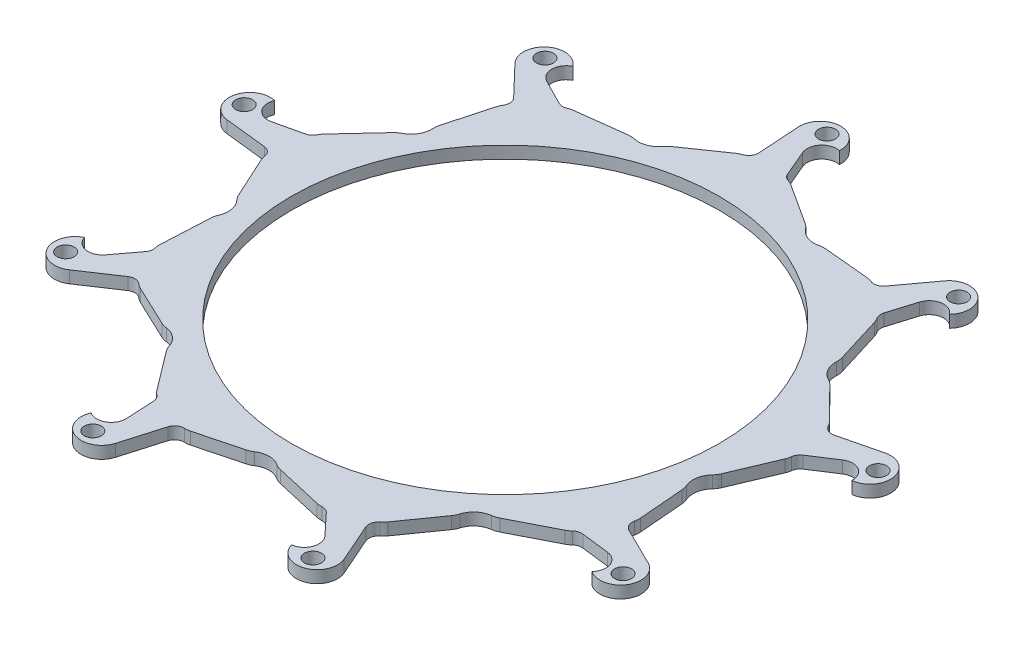
SolidWorks part; units mm, degrees
ref_plane "Front Plane" through (0, 0, 0) normal (0, 0, 1) x (1, 0, 0)
ref_plane "Top Plane" through (0, 0, 0) normal (0, 1, 0) x (1, 0, 0)
ref_plane "Right Plane" through (0, 0, 0) normal (1, 0, 0) x (0, 0, -1)
sketch "Sketch1" plane through (0, 0, 0) normal (0, 1, 0) x (1, 0, 0)
  circle A0 centre (0, 0) radius 55.9594
  circle A1 centre (0, 0) radius 68.6594
  dimension "D1" = 111.9188
  dimension "D2" = 12.7
extrude "Boss-Extrude1" add sketch "Sketch1" along normal blind 3.175
sketch "Sketch2" plane through (0, 3.175, 0) normal (0, 1, 0) x (1, 0, 0)
  line L0 (0, 0) -> (0, 135.9318) construction
  line L1 (0, 0) -> (-4.4905, 68.5124) construction
  line L2 (0, 0) -> (8.8904, 135.6408) construction
  line L3 (-4.6537, 71.0017) -> (-5.3728, 81.9729)
  line L4 (3.8894, 69.9338) -> (0.9836, 76.7774)
  line L5 (-4.6537, 71.0017) -> (-8.8904, 135.6408) construction
  arc A0 (-6.9318, 68.3086) -> (-4.6537, 71.0017) centre (-7.1883, 70.8356) ccw
  circle A1 centre (0, 0) radius 68.6594 construction
  arc A2 (5.3728, 81.9729) -> (-5.3728, 81.9729) centre (0, 82.3251) ccw
  arc A3 (5.3728, 81.9729) -> (0.9836, 76.7774) centre (4.4905, 78.2665) ccw
  arc A4 (6.0052, 68.3963) -> (-6.9318, 68.3086) centre (0, 0) ccw
  arc A5 (3.8894, 69.9338) -> (6.0052, 68.3963) centre (6.2274, 70.9265) ccw
  point P10 (4.4905, 68.5124)
  dimension "D2" = 7.62
  dimension "D3" = 19.05
  dimension "D4" = 5.3843
  dimension "D5" = 5.08
  dimension "D6" = 2.54
  dimension "D7" = 64.77
  dimension "D1" = 7.5
extrude "Boss-Extrude2" add sketch "Sketch2" against normal blind 3.175
pattern_circular "CirPattern1" count 9 over 360 about axis through (0, 0, 0) along (0, 1, 0) of "Boss-Extrude2"
sketch "Sketch3" plane through (0, 3.175, 0) normal (0, 1, 0) x (1, 0, 0)
  line L0 (0, 0) -> (0, 87.7094) construction
  circle A0 centre (0, 84.1322) radius 2.2225
  arc A4 (5.3728, 81.9729) -> (0.9836, 76.7774) centre (4.4905, 78.2665) ccw construction
  arc A5 (5.3728, 81.9729) -> (-5.3728, 81.9729) centre (0, 82.3251) ccw construction
  dimension "D1" = 4.445
  dimension "D2" = 1.3547
  dimension "D3" = 1.3547
extrude "Cut-Extrude6" cut sketch "Sketch3" against normal through all
pattern_circular "CirPattern10" count 9 over 360 about axis through (0, 0, 0) along (0, 1, 0) of "Cut-Extrude6"
sketch "Sketch4" plane through (0, 3.175, 0) normal (0, 1, 0) x (1, 0, 0)
  line L0 (0, 0) -> (0, 105.2172) construction
  line L1 (0, 0) -> (35.9864, 98.8719) construction
  line L2 (21.0579, 57.8562) -> (6.0052, 68.3963) construction
  line L3 (18.2672, 60.4622) -> (6.0052, 68.3963)
  line L4 (24.8709, 58.0587) -> (38.5978, 56.7831)
  arc A0 (38.5978, 56.7831) -> (6.0052, 68.3963) centre (0, 0) ccw construction
  arc A1 (38.5978, 56.7831) -> (6.0052, 68.3963) centre (0, 0) ccw
  arc A2 (5.3728, 81.9729) -> (-5.3728, 81.9729) centre (0, 82.3251) ccw construction
  arc A3 (5.3728, 81.9729) -> (-5.3728, 81.9729) centre (0, 82.3251) ccw construction
  arc A4 (18.2672, 60.4622) -> (24.8709, 58.0587) centre (22.9646, 63.0948) ccw
  dimension "D2" = 75
  dimension "D3" = 5.3848
  dimension "D1" = 20
  dimension "D4" = 14.605
extrude "Cut-Extrude7" cut sketch "Sketch4" against normal through all
pattern_circular "CirPattern12" count 9 over 360 about axis through (0, 0, 0) along (0, 1, 0) of "Cut-Extrude7"
fillet "Fillet1" radius 5.08 36 edges at (48.5645, 1.5875, -48.5345) (52.8578, 1.5875, -34.5748) (56.3716, 1.5875, -28.4888) (66.0671, 1.5875, -18.6882) (68.4, 1.5875, -5.9629) (62.7157, 1.5875, 7.4905) (61.4954, 1.5875, 14.4112) (62.6229, 1.5875, 28.1511) (56.2303, 1.5875, 39.3988) (43.2282, 1.5875, 46.051) (37.8448, 1.5875, 50.5681) (29.8767, 1.5875, 61.8182) (17.7499, 1.5875, 66.3254) (3.5137, 1.5875, 63.0636) (-3.5137, 1.5875, 63.0636) (-16.8491, 1.5875, 66.5599) (-29.0359, 1.5875, 62.2176) (-37.8448, 1.5875, 50.5681) (-43.2282, 1.5875, 46.051) (-55.691, 1.5875, 40.1574) (-62.2355, 1.5875, 28.9975) (-61.4954, 1.5875, 14.4112) (-62.7157, 1.5875, 7.4905) (-68.4745, 1.5875, -5.0351) (-66.3144, 1.5875, -17.7908) (-56.3716, 1.5875, -28.4888) (-52.8578, 1.5875, -34.5748) (-49.218, 1.5875, -47.8717) (-39.364, 1.5875, -56.2546) (-24.8709, 1.5875, -58.0587) (-18.2672, 1.5875, -60.4622) (-6.9318, 1.5875, -68.3086) (38.5978, 1.5875, -56.7831) (24.8709, 1.5875, -58.0587) (18.2672, 1.5875, -60.4622) (6.0052, 1.5875, -68.3963)
